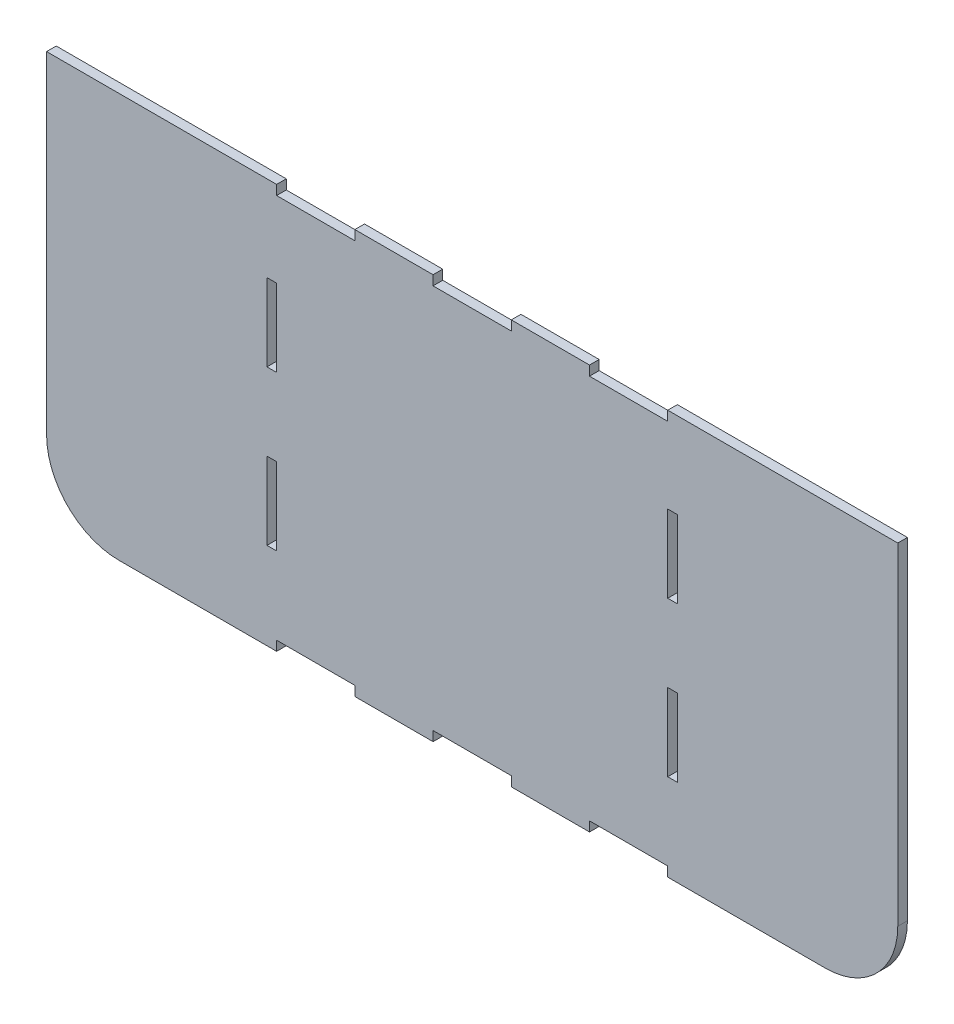
SolidWorks part; units mm, degrees
material "A-Glass Fiber"
ref_plane "Front Plane" through (0, 0, 0) normal (0, 0, 1) x (1, 0, 0)
ref_plane "Top Plane" through (0, 0, 0) normal (0, 1, 0) x (1, 0, 0)
ref_plane "Right Plane" through (0, 0, 0) normal (1, 0, 0) x (0, 0, -1)
sketch "Sketch1" plane through (0, 0, 0) normal (0, 0, 1) x (1, 0, 0)
  line L0 (0, 0) -> (1345.4471, 0)
  line L1 (212.2829, -469.9) -> (1133.1642, -469.9)
  line L2 (0, 0) -> (188.5098, -454.2888)
  line L3 (1345.4471, 0) -> (1156.9372, -454.2888)
  spline S1 degree 3 poles (1156.9372, -454.2888) (1155.9652, -456.6313) (1154.631, -458.8169) (1152.2259, -461.6935) (1151.3551, -462.5908) (1149.4733, -464.2609) (1148.4599, -465.0331) (1146.3603, -466.4012) (1145.2664, -467.0047) (1142.9909, -468.0521) (1141.799, -468.4985) (1138.1745, -469.5606) (1135.6993, -469.9116) (1133.1642, -469.9) knots 0 0 0 0 0.25 0.25 0.375 0.375 0.5 0.5 0.625 0.625 0.75 0.75 1 1 1 1
  spline S2 degree 3 poles (188.5098, -454.2888) (189.4819, -456.6313) (190.8161, -458.8169) (193.2211, -461.6935) (194.092, -462.5908) (195.9737, -464.2609) (196.9872, -465.0331) (199.0868, -466.4012) (200.1807, -467.0047) (202.4562, -468.0521) (203.6481, -468.4985) (207.2726, -469.5606) (209.7478, -469.9116) (212.2829, -469.9) knots 0 0 0 0 0.25 0.25 0.375 0.375 0.5 0.5 0.625 0.625 0.75 0.75 1 1 1 1
  dimension "D1" = 112.536
  dimension "D2" = 112.536
  dimension "D3" = 920.8813
  dimension "D4" = 469.9
extrude "Boss-Extrude1" add sketch "Sketch1" along normal blind 10.16
ref_plane "Plane1" through (672.7235, 0, 0) normal (1, 0, 0) x (0, 0, -1)
sketch "Sketch2" plane through (0, 0, 10.16) normal (0, 0, 1) x (1, 0, 0)
  line L0 (467.0082, -378.4231) -> (467.0082, -297.1061) construction
  line L1 (467.0082, -297.1061) -> (456.8417, -297.1061) construction
  line L2 (456.8417, -297.1061) -> (456.8417, -378.4231) construction
  line L3 (456.8417, -378.4231) -> (467.0082, -378.4231) construction
  line L4 (878.4388, -297.1061) -> (878.4388, -378.4231) construction
  line L5 (878.4388, -378.4231) -> (888.6053, -378.4231) construction
  line L6 (888.6053, -378.4231) -> (888.6053, -297.1061) construction
  line L7 (888.6053, -297.1061) -> (878.4388, -297.1061) construction
  line L8 (878.4388, -134.4722) -> (878.4388, -215.7892) construction
  line L9 (878.4388, -215.7892) -> (888.6053, -215.7892) construction
  line L10 (888.6053, -215.7892) -> (888.6053, -134.4722) construction
  line L11 (888.6053, -134.4722) -> (878.4388, -134.4722) construction
  line L24 (467.0082, -215.7892) -> (467.0082, -134.4722) construction
  line L25 (467.0082, -134.4722) -> (456.8417, -134.4722) construction
  line L26 (456.8417, -134.4722) -> (456.8417, -215.7892) construction
  line L27 (456.8417, -215.7892) -> (467.0082, -215.7892) construction
  line L28 (878.4388, -469.9) -> (878.4388, -459.74) construction
  line L29 (878.4388, -459.74) -> (796.1675, -459.74) construction
  line L30 (796.1675, -469.9) -> (796.1675, -459.74) construction
  line L31 (713.8592, -469.9) -> (713.8592, -459.74) construction
  line L32 (631.5879, -459.74) -> (713.8592, -459.74) construction
  line L33 (631.5879, -469.9) -> (631.5879, -459.74) construction
  line L34 (467.0082, -469.9) -> (467.0082, -459.74) construction
  line L35 (549.2795, -469.9) -> (549.2795, -459.74) construction
  line L36 (467.0082, -459.74) -> (549.2795, -459.74) construction
  line L37 (467.0082, -378.4231) -> (467.0082, -297.1061)
  line L38 (467.0082, -297.1061) -> (456.8417, -297.1061)
  line L39 (456.8417, -297.1061) -> (456.8417, -378.4231)
  line L40 (456.8417, -378.4231) -> (467.0082, -378.4231)
  line L41 (878.4388, -297.1061) -> (878.4388, -378.4231)
  line L42 (878.4388, -378.4231) -> (888.6053, -378.4231)
  line L43 (888.6053, -378.4231) -> (888.6053, -297.1061)
  line L44 (888.6053, -297.1061) -> (878.4388, -297.1061)
  line L45 (878.4388, -134.4722) -> (878.4388, -215.7892)
  line L46 (878.4388, -215.7892) -> (888.6053, -215.7892)
  line L47 (888.6053, -215.7892) -> (888.6053, -134.4722)
  line L48 (888.6053, -134.4722) -> (878.4388, -134.4722)
  line L61 (467.0082, -215.7892) -> (467.0082, -134.4722)
  line L62 (467.0082, -134.4722) -> (456.8417, -134.4722)
  line L63 (456.8417, -134.4722) -> (456.8417, -215.7892)
  line L64 (456.8417, -215.7892) -> (467.0082, -215.7892)
  line L65 (878.4388, -469.9) -> (878.4388, -459.74)
  line L66 (878.4388, -459.74) -> (796.1675, -459.74)
  line L67 (796.1675, -469.9) -> (796.1675, -459.74)
  line L68 (713.8592, -469.9) -> (713.8592, -459.74)
  line L69 (631.5879, -459.74) -> (713.8592, -459.74)
  line L70 (631.5879, -469.9) -> (631.5879, -459.74)
  line L71 (467.0082, -469.9) -> (467.0082, -459.74)
  line L72 (549.2795, -469.9) -> (549.2795, -459.74)
  line L73 (467.0082, -459.74) -> (549.2795, -459.74)
  line L74 (467.0082, -469.9) -> (549.2795, -469.9)
  line L75 (631.5879, -469.9) -> (713.8592, -469.9)
  line L76 (796.1675, -469.9) -> (878.4388, -469.9)
extrude "Cut-Extrude2" cut sketch "Sketch2" against normal blind 137.414
sketch "Sketch4" plane through (0, 0, 10.16) normal (0, 0, 1) x (1, 0, 0)
  line L0 (0, 0) -> (1345.4471, 0)
  line L1 (1345.4471, 0) -> (1327.0023, -44.45)
  line L2 (1156.9372, -454.2888) -> (1345.4471, 0) construction
  line L3 (1327.0023, -44.45) -> (18.4448, -44.45)
  line L4 (0, 0) -> (188.5098, -454.2888) construction
  line L5 (18.4448, -44.45) -> (0, 0)
  dimension "D1" = 44.45
extrude "Cut-Extrude3" cut sketch "Sketch4" against normal through all
sketch "Sketch5" plane through (0, 0, 10.16) normal (0, 0, 1) x (1, 0, 0)
  line L0 (672.7235, -11.176) -> (672.7235, 11.176) construction
  line L1 (713.8715, -54.61) -> (631.5755, -54.61)
  line L2 (713.8715, -54.61) -> (713.8715, -44.45)
  line L3 (713.8715, -44.45) -> (631.5755, -44.45)
  line L4 (631.5755, -54.61) -> (631.5755, -44.45)
  line L5 (713.8715, -54.61) -> (631.5755, -44.45) construction
  line L6 (713.8715, -44.45) -> (631.5755, -54.61) construction
  line L7 (18.4448, -44.45) -> (1327.0023, -44.45) construction
  line L9 (631.5755, -44.45) -> (549.2795, -44.45)
  line L10 (631.5755, -44.45) -> (631.5755, -54.61)
  line L11 (631.5755, -54.61) -> (549.2795, -54.61)
  line L12 (549.2795, -44.45) -> (549.2795, -54.61)
  line L13 (549.2795, -44.45) -> (466.9835, -44.45)
  line L14 (549.2795, -44.45) -> (549.2795, -54.61)
  line L15 (549.2795, -54.61) -> (466.9835, -54.61)
  line L16 (466.9835, -44.45) -> (466.9835, -54.61)
  line L17 (713.8715, -44.45) -> (796.1675, -44.45)
  line L18 (713.8715, -44.45) -> (713.8715, -54.61)
  line L19 (713.8715, -54.61) -> (796.1675, -54.61)
  line L20 (796.1675, -44.45) -> (796.1675, -54.61)
  line L21 (796.1675, -44.45) -> (878.4635, -44.45)
  line L22 (796.1675, -44.45) -> (796.1675, -54.61)
  line L23 (796.1675, -54.61) -> (878.4635, -54.61)
  line L24 (878.4635, -44.45) -> (878.4635, -54.61)
  point P0 (672.7235, -49.53)
  line M26 (1327.0023, -44.45) -> (18.4448, -44.45)
  dimension "D1" = 82.296
  dimension "D2" = 10.16
extrude "Cut-Extrude4" cut sketch "Sketch5" against normal through all contours L16 L15 L12 M26 | L4 L1 L2 M26 | L24 L20 L23 M26
sketch "Sketch6" plane through (0, 0, 10.16) normal (0, 0, 1) x (1, 0, 0)
  line L0 (192.8075, -448.0779) -> (224.9829, -469.9)
  line L2 (212.2829, -469.9) -> (467.0082, -469.9) construction
  line L4 (56.5448, -44.45) -> (56.5448, -119.699)
  line L5 (24.3099, -42.0162) -> (194.3749, -451.8551)
  line L6 (56.5448, -119.699) -> (192.8075, -448.0779)
  line L7 (18.4448, -44.45) -> (466.9835, -44.45) construction
  line L9 (56.5448, -44.45) -> (-120.2389, 37.3825)
  line L10 (-120.2389, 37.3825) -> (-59.5107, -242.3351)
  line L11 (-59.5107, -242.3351) -> (232.0802, -549.7664)
  line L12 (224.9829, -469.9) -> (232.0802, -549.7664)
  line L13 (672.7235, -54.61) -> (672.7235, -459.74) construction
  line L14 (713.8715, -54.61) -> (631.5755, -54.61) construction
  line L15 (713.8592, -459.74) -> (631.5879, -459.74) construction
  line L16 (1120.4642, -469.9) -> (1113.3668, -549.7664)
  line L17 (1404.9578, -242.3351) -> (1113.3668, -549.7664)
  line L18 (1465.686, 37.3825) -> (1404.9578, -242.3351)
  line L19 (1288.9023, -44.45) -> (1465.686, 37.3825)
  line L20 (1288.9023, -119.699) -> (1152.6395, -448.0779)
  line L21 (1288.9023, -44.45) -> (1288.9023, -119.699)
  line L22 (1152.6395, -448.0779) -> (1120.4642, -469.9)
  dimension "D1" = 12.7
  dimension "D2" = 38.1
  dimension "D3" = 6.35
extrude "Cut-Extrude5" cut sketch "Sketch6" against normal through all
sketch "Sketch7" plane through (0, 0, 10.16) normal (0, 0, 1) x (1, 0, 0)
  line L0 (224.9829, -469.9) -> (467.0082, -469.9) construction
  line L1 (301.1829, -469.9) -> (-145.5373, -469.9)
  line L2 (224.9829, -393.7) -> (224.9829, 127.8863)
  line L3 (224.9829, 127.8863) -> (-145.5373, 127.8863)
  line L4 (-145.5373, -469.9) -> (-145.5373, 127.8863)
  line L5 (1044.2642, -469.9) -> (1351.8588, -469.9)
  line L6 (1120.4642, -393.7) -> (1120.4642, 23.6984)
  line L7 (1120.4642, 23.6984) -> (1351.8588, 23.6984)
  line L8 (1351.8588, -469.9) -> (1351.8588, 23.6984)
  line L9 (672.7235, -459.74) -> (672.7235, 43.7275) construction
  line L10 (713.8592, -459.74) -> (631.5879, -459.74) construction
  line L11 (672.7235, -5.588) -> (672.7235, 5.588) construction
  arc A0 (224.9829, -393.7) -> (301.1829, -469.9) centre (301.1829, -393.7) ccw
  arc A1 (1120.4642, -393.7) -> (1044.2642, -469.9) centre (1044.2642, -393.7) cw
  dimension "D1" = 152.4
extrude "Cut-Extrude6" cut sketch "Sketch7" against normal blind 25.4
